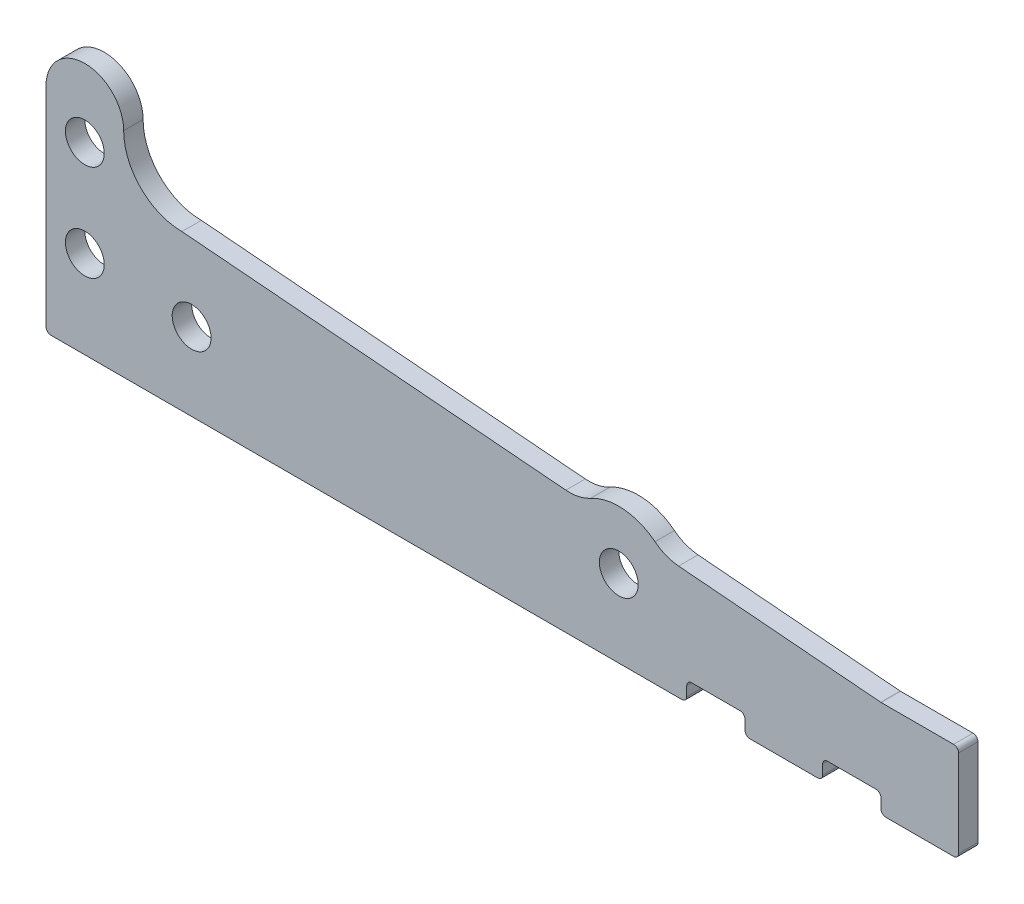
SolidWorks part; units mm, degrees
ref_plane "Front Plane" through (0, 0, 0) normal (0, 0, 1) x (1, 0, 0)
ref_plane "Top Plane" through (0, 0, 0) normal (0, 1, 0) x (1, 0, 0)
ref_plane "Right Plane" through (0, 0, 0) normal (1, 0, 0) x (0, 0, -1)
sketch "Sketch1" plane through (0, 0, 0) normal (0, 0, 1) x (1, 0, 0)
  line L0 (3.175, 19.05) -> (3.175, 0) construction
  line L1 (0, 0) -> (6.35, 0) construction
  line L2 (0, 0) -> (0, 19.05)
  line L3 (0, 19.05) -> (6.35, 19.05)
  line L4 (6.35, 0) -> (6.35, 19.05) construction
  line L5 (3.175, 13.462) -> (3.175, 5.588) construction
  line L6 (6.35, 0) -> (68.2625, 0) construction
  line L9 (0, 0) -> (0, -1.5875)
  line L11 (68.2625, -1.5875) -> (68.2625, 0)
  line L12 (0, 19.05) -> (-1.5875, 19.05) construction
  line L13 (-1.5875, 19.05) -> (-1.5875, -1.5875) construction
  line L14 (-1.5875, -1.5875) -> (0, -1.5875) construction
  line L15 (68.2625, 11.1125) -> (6.35, 11.1125) construction
  line L16 (68.2625, 0) -> (68.2625, 11.1125) construction
  line L17 (11.1125, 11.1125) -> (68.2625, 6.35)
  line L18 (68.2625, 6.35) -> (68.2625, 0)
  line L19 (68.2625, 6.35) -> (74.6125, 6.35)
  line L20 (74.6125, 6.35) -> (74.6125, -1.5875)
  line L21 (74.6125, -1.5875) -> (68.2625, -1.5875)
  line L22 (68.2625, 0) -> (63.5, 0)
  line L23 (63.5, 0) -> (63.5, -1.5875)
  line L24 (63.5, -1.5875) -> (57.15, -1.5875)
  line L25 (57.15, -1.5875) -> (57.15, 0)
  line L26 (57.15, 0) -> (52.3875, 0)
  line L27 (52.3875, 0) -> (52.3875, -1.5875)
  line L28 (52.3875, -1.5875) -> (0, -1.5875)
  line L29 (11.9062, -1.5875) -> (11.9062, 4.7625) construction
  line L30 (46.8312, -1.5875) -> (46.8312, 4.7625) construction
  circle A0 centre (3.175, 13.462) radius 1.5875
  circle A1 centre (3.175, 5.588) radius 1.5875
  circle A2 centre (3.175, 15.875) radius 3.175
  circle A3 centre (3.175, 3.175) radius 3.175
  circle A4 centre (11.1125, 15.875) radius 4.7625
  circle A5 centre (11.9062, 4.7625) radius 1.5875
  circle A7 centre (46.8312, 4.7625) radius 1.5875
  circle A8 centre (46.8312, 4.7625) radius 4.7625
  point P11 (3.175, 9.525)
  point P12 (3.175, 9.525)
  point P30 (6.35, 15.875)
  dimension "D1" = 19.05
  dimension "D2" = 3.175
  dimension "D8" = 11.1125
  dimension "D9" = 6.35
  dimension "D10" = 6.35
  dimension "D13" = 5.5562
  dimension "D3" = 6.35
  dimension "D4" = 7.874
  dimension "D5" = 1.5875
  dimension "D6" = 69.85
  dimension "D7" = 1.5875
  dimension "D11" = 15.875
  dimension "D12" = 6.35
  dimension "D14" = 5.5562
  dimension "D15" = 6.35
extrude "Boss-Extrude1" add sketch "Sketch1" along normal blind 1.5875
fillet "Fillet1" radius 0.4064 12 edges at (68.2625, 6.35, 0.7937) (74.6125, 6.35, 0.7937) (63.5, 0, 0.7937) (52.3875, 0, 0.7937) (74.6125, -1.5875, 0.7937) (52.3875, -1.5875, 0.7937) (63.5, -1.5875, 0.7937) (68.2625, -1.5875, 0.7937) (68.2625, 0, 0.7937) (57.15, 0, 0.7937) (57.15, -1.5875, 0.7937) (0, -1.5875, 0.7937)
fillet "Fillet2" radius 3.5719 2 edges at (43.7487, 8.3928, 0.7937) (50.4722, 7.8325, 0.7937)
